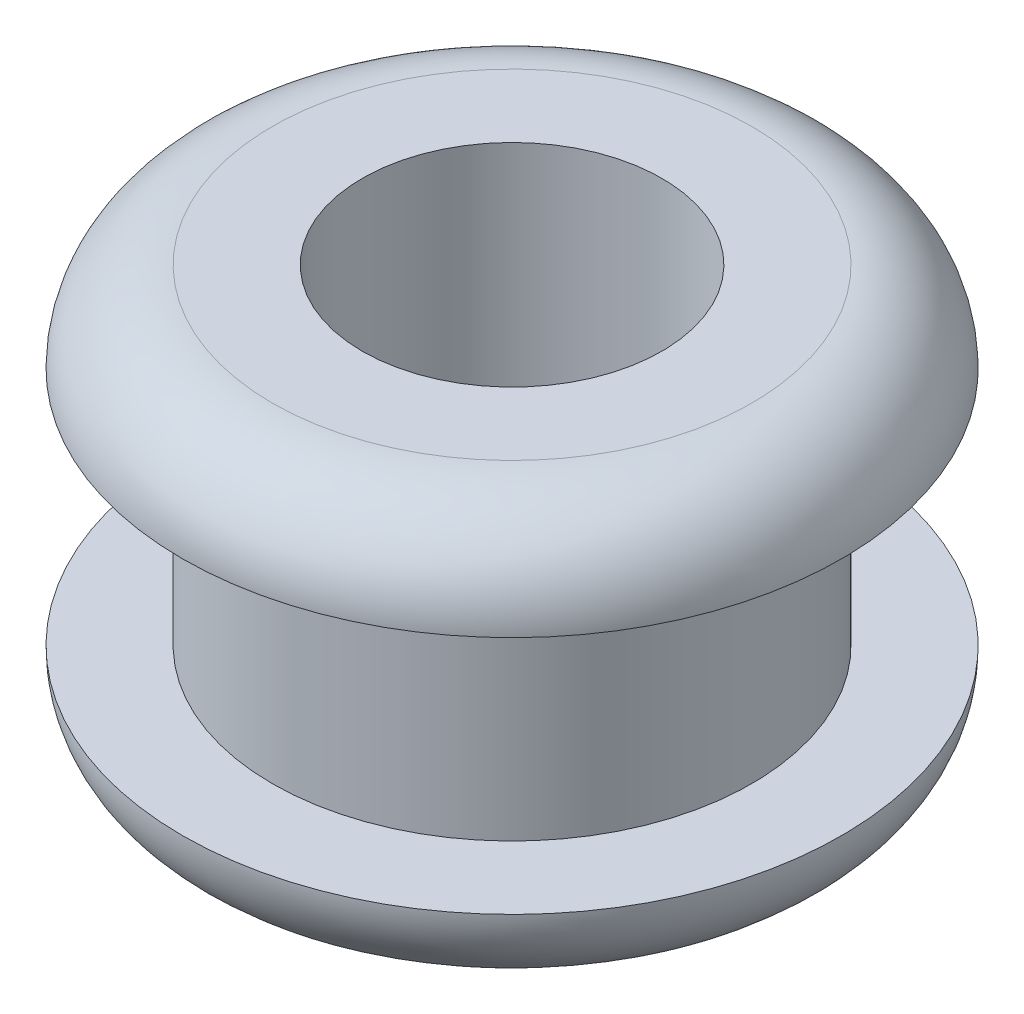
SolidWorks part; units mm, degrees
material "Rubber"
ref_plane "Front Plane" through (0, 0, 0) normal (0, 0, 1) x (1, 0, 0)
ref_plane "Top Plane" through (0, 0, 0) normal (0, 1, 0) x (1, 0, 0)
ref_plane "Right Plane" through (0, 0, 0) normal (1, 0, 0) x (0, 0, -1)
sketch "Sketch1" plane through (0, 0, 0) normal (0, 0, 1) x (1, 0, 0)
  line L0 (0, 0) -> (0, -47.2537) construction
  line L1 (3.9688, 0) -> (6.35, 0)
  line L2 (8.7312, -2.3812) -> (6.35, -2.3812)
  line L3 (6.35, -2.3812) -> (6.35, -8.7312)
  line L4 (6.35, -8.7312) -> (8.7312, -8.7312)
  line L5 (6.35, -11.1125) -> (3.9688, -11.1125)
  line L6 (3.9688, -11.1125) -> (3.9688, 0)
  arc A0 (6.35, 0) -> (8.7312, -2.3812) centre (6.35, -2.3812) cw
  arc A1 (8.7312, -8.7312) -> (6.35, -11.1125) centre (6.35, -8.7312) cw
  dimension "D1" = 12.7
  dimension "D2" = 7.9375
  dimension "D3" = 6.35
  dimension "D4" = 17.4625
revolve "Revolve1" add sketch "Sketch1" angle 360 about L0
